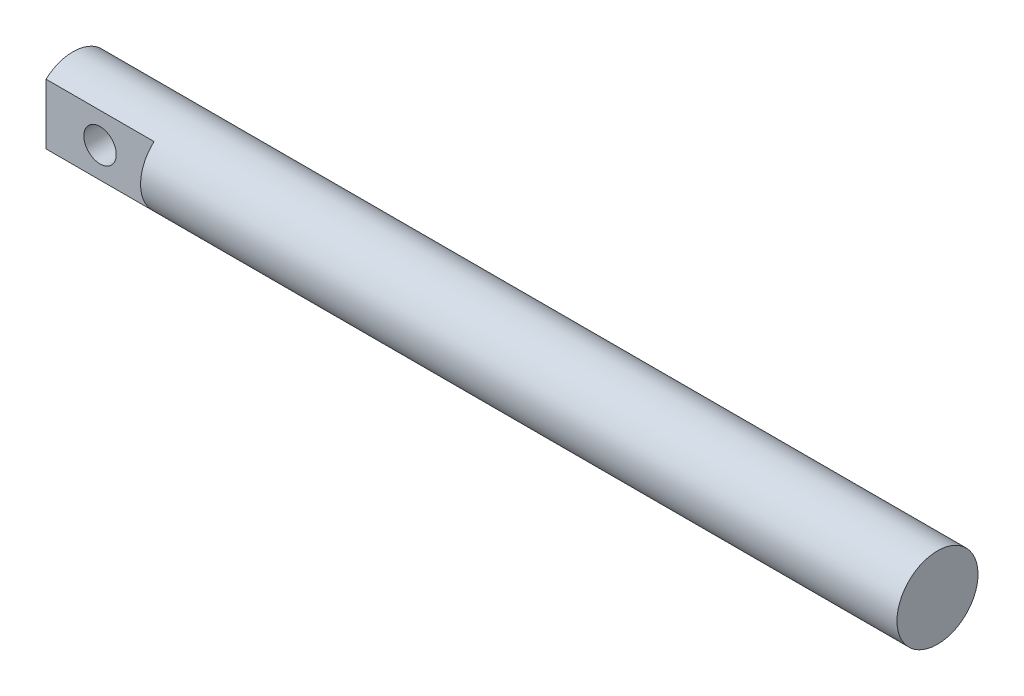
SolidWorks part; units mm, degrees
ref_plane "Plane1" through (0, 0, 0) normal (0, 0, 1) x (1, 0, 0)
ref_plane "Plane2" through (0, 0, 0) normal (0, 1, 0) x (1, 0, 0)
ref_plane "Plane3" through (0, 0, 0) normal (1, 0, 0) x (0, 0, -1)
other "Configuration Table"
sketch "Sketch2" plane through (0, 0, 0) normal (-1, 0, 0) x (0, 0, 1)
  circle A1 centre (0, 0) radius 4.7625
extrude "Base-Extrude" add sketch "Sketch2" along normal blind 101.6
sketch "Sketch4" plane through (0, 0, 0) normal (0, 1, 0) x (1, 0, 0)
  line L0 (-109.22, 12.7) -> (-88.9, 12.7)
  line L1 (-109.22, 12.7) -> (-109.22, -12.7)
  line L2 (-88.9, 3.175) -> (-104.14, 3.175)
  line L3 (-88.9, 3.175) -> (-88.9, 12.7)
  line L4 (-104.14, -3.175) -> (-88.9, -3.175)
  line L5 (-101.6, 4.7625) -> (-101.6, -4.7625) construction
  line L6 (-88.9, -12.7) -> (-109.22, -12.7)
  line L7 (-88.9, -12.7) -> (-88.9, -3.175)
  line L10 (-104.14, 3.175) -> (-104.14, -3.175)
  point P2 (-104.14, 0)
  dimension "D1" = 6.35
  dimension "D2" = 12.7
  dimension "D3" = 5.08
  dimension "D4" = 25.4
  dimension "D5" = 2.54
extrude "Cut-Extrude1" cut sketch "Sketch4" against normal through all and the other way through all
sketch "Sketch5" plane through (0, 0, 3.175) normal (0, 0, 1) x (1, 0, 0)
  line L1 (-101.6, -3.5498) -> (-101.6, 3.5498) construction
  circle A0 centre (-95.25, 0) radius 1.905
  point P2 (-101.6, 0)
  dimension "D2" = 3.81
  dimension "D1" = 6.35
extrude "Cut-Extrude2" cut sketch "Sketch5" against normal through all
